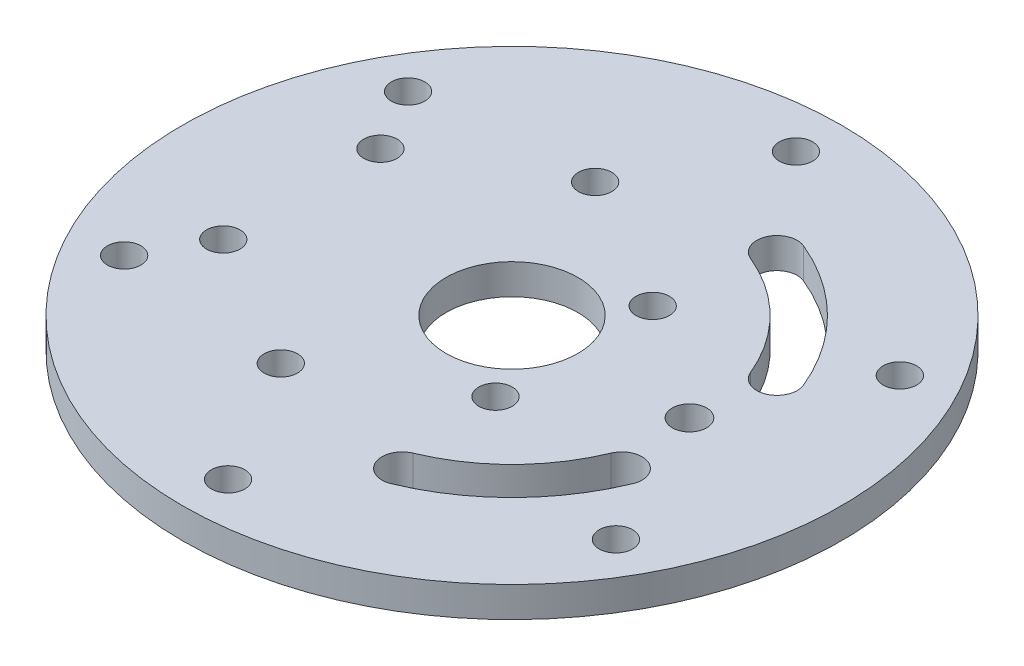
SolidWorks part; units mm, degrees
material "环氧树脂,未充填"
ref_plane "前视基准面" through (0, 0, 0) normal (0, 0, 1) x (1, 0, 0)
ref_plane "上视基准面" through (0, 0, 0) normal (0, 1, 0) x (1, 0, 0)
ref_plane "右视基准面" through (0, 0, 0) normal (1, 0, 0) x (0, 0, -1)
sketch "草图1" plane through (0, 0, 0) normal (0, 1, 0) x (1, 0, 0)
  line L0 (-32.0969, 0) -> (32.0969, 0) construction
  line L1 (0, -35.9181) -> (0, 35.9181) construction
  line L2 (24.4669, 0) -> (-39.0669, 0) construction
  line L7 (-7.3, -11.8861) -> (-7.3, 11.8861) construction
  line L8 (0, -11.0253) -> (0, 11.0253) construction
  line L9 (0, 0) -> (16.3192, -16.3192) construction
  circle A0 centre (0, 0) radius 32.5
  circle A1 centre (0, 0) radius 28 construction
  circle A3 centre (-7.3, 0) radius 15.5 construction
  circle A4 centre (0, 0) radius 6.5
  circle A11 centre (0, 0) radius 17.5 construction
  circle A12 centre (-7.3, 15.5) radius 1.65
  circle A13 centre (6.1234, 7.75) radius 1.65
  circle A14 centre (6.1234, -7.75) radius 1.65
  circle A15 centre (-7.3, -15.5) radius 1.65
  circle A16 centre (-20.7234, -7.75) radius 1.65
  circle A17 centre (-20.7234, 7.75) radius 1.65
  circle A18 centre (-7.3, 0) radius 18.5 construction
  circle A19 centre (17.5, 0) radius 1.7
  circle A20 centre (0, 28) radius 1.65
  circle A21 centre (24.2487, 14) radius 1.65
  circle A22 centre (24.2487, -14) radius 1.65
  circle A23 centre (0, -28) radius 1.65
  circle A24 centre (-24.2487, -14) radius 1.65
  circle A25 centre (-24.2487, 14) radius 1.65
  arc A26 (7.6537, -18.4776) -> (18.4776, -7.6537) centre (0, 0) ccw construction
  arc A27 (8.419, -20.3253) -> (20.3253, -8.419) centre (0, 0) ccw
  arc A28 (6.8883, -16.6298) -> (16.6298, -6.8883) centre (0, 0) ccw
  arc A29 (6.8883, -16.6298) -> (8.419, -20.3253) centre (7.6537, -18.4776) ccw
  arc A30 (20.3253, -8.419) -> (16.6298, -6.8883) centre (18.4776, -7.6537) ccw
  arc A31 (7.6537, 18.4776) -> (18.4776, 7.6537) centre (0, 0) cw construction
  arc A32 (8.419, 20.3253) -> (20.3253, 8.419) centre (0, 0) cw
  arc A33 (6.8883, 16.6298) -> (16.6298, 6.8883) centre (0, 0) cw
  arc A34 (6.8883, 16.6298) -> (8.419, 20.3253) centre (7.6537, 18.4776) cw
  arc A35 (20.3253, 8.419) -> (16.6298, 6.8883) centre (18.4776, 7.6537) cw
  point P4 (0, 0)
  point P8 (0, 0)
  point P16 (-7.3, 0)
  point P19 (-7.3, 0)
  point P22 (0, 0)
  point P34 (0, 0)
  point P38 (-7.3, 0)
  point P55 (0, 0)
  point P56 (14.1421, -14.1421)
  point P67 (14.1421, 14.1421)
  dimension "D1" = 31
  dimension "D4" = 65
  dimension "D5" = 56
  dimension "D7" = 3.3
  dimension "D8" = 35
  dimension "D9" = 37
  dimension "D2" = 13
  dimension "D10" = 3.4
  dimension "D12" = 3.3
  dimension "D14" = 20
  dimension "D15" = 4
  dimension "D3" = 7.3
  dimension "D13" = 45
  dimension "D6" = 6
  dimension "D11" = 6
extrude "凸台-拉伸1" add sketch "草图1" along normal blind 3
